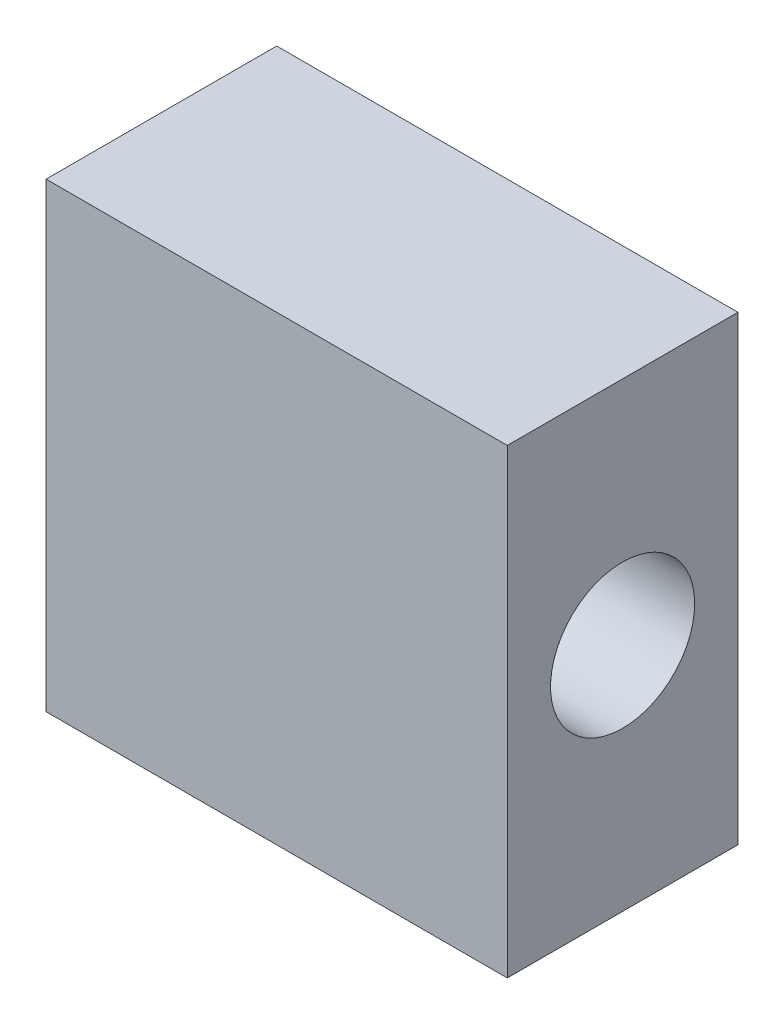
SolidWorks part; units mm, degrees
ref_plane "Front Plane" through (0, 0, 0) normal (0, 0, 1) x (1, 0, 0)
ref_plane "Top Plane" through (0, 0, 0) normal (0, 1, 0) x (1, 0, 0)
ref_plane "Right Plane" through (0, 0, 0) normal (1, 0, 0) x (0, 0, -1)
sketch "Sketch1" plane through (0, 0, 0) normal (0, 0, 1) x (1, 0, 0)
  line L0 (0, 0) -> (50.8, 50.8) construction
  line L1 (0, 0) -> (50.8, 0)
  line L2 (0, 0) -> (0, 50.8)
  line L3 (0, 50.8) -> (50.8, 50.8)
  line L4 (50.8, 0) -> (50.8, 50.8)
  circle A0 centre (9.6846, 9.6846) radius 6.35 construction
  circle A1 centre (41.1154, 41.1154) radius 6.35 construction
  circle A2 centre (25.4, 25.4) radius 22.225 construction
  point P11 (0, 0)
  dimension "D2" = 44.45
  dimension "D3" = 12.7
  dimension "D1" = 50.8
extrude "Boss-Extrude1" add sketch "Sketch1" along normal blind 25.4
sketch "Sketch2" plane through (50.8, 0, 0) normal (1, 0, 0) x (0, 0, -1)
  line L0 (-25.4, 50.8) -> (0, 0) construction
  circle A0 centre (-12.7, 25.4) radius 7.9375
  point P6 (0, 0)
  point P7 (0, 0)
  dimension "D1" = 15.875
extrude "Cut-Extrude1" cut sketch "Sketch2" against normal blind 25.4
